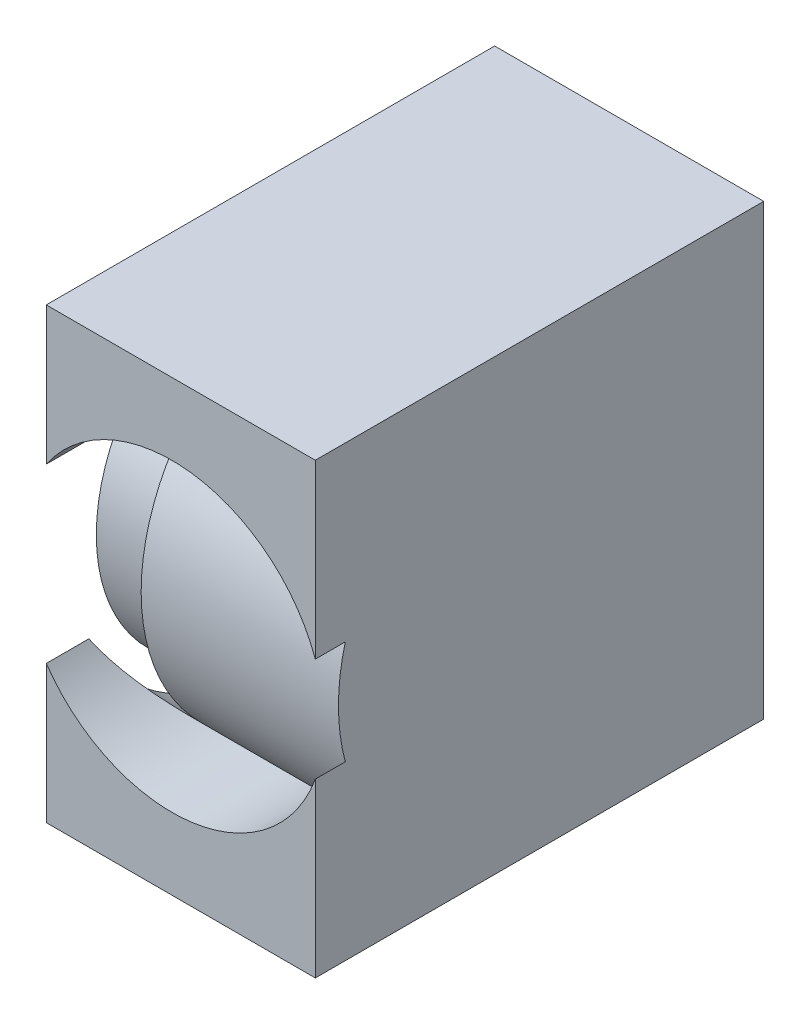
SolidWorks part; units mm, degrees
ref_plane "Front Plane" through (0, 0, 0) normal (0, 0, 1) x (1, 0, 0)
ref_plane "Top Plane" through (0, 0, 0) normal (0, 1, 0) x (1, 0, 0)
ref_plane "Right Plane" through (0, 0, 0) normal (1, 0, 0) x (0, 0, -1)
sketch "Sketch1" plane through (0, 0, 0) normal (1, 0, 0) x (0, 0, -1)
  line L1 (-12.5, 12.5) -> (12.5, 12.5)
  line L2 (-12.5, 12.5) -> (-12.5, -12.5)
  line L3 (-12.5, -12.5) -> (12.5, -12.5)
  line L4 (12.5, 12.5) -> (12.5, -12.5)
  line L5 (-12.5, 12.5) -> (12.5, -12.5) construction
  line L6 (-12.5, -12.5) -> (12.5, 12.5) construction
  point P4 (0, 0)
  dimension "D1" = 25
  dimension "D2" = 25
extrude "Boss-Extrude1" add sketch "Sketch1" along normal blind 15
sketch "Sketch2" plane through (0, 0, 0) normal (-1, 0, 0) x (0, 0, 1)
  circle A0 centre (0, 0) radius 9.71
  circle A1 centre (0, 0) radius 11.21
  dimension "D1" = 19.42
  dimension "D2" = 22.42
extrude "Cut-Extrude1" cut sketch "Sketch2" against normal blind 4
sketch "Sketch4" plane through (0, 0, 12.5) normal (0, 0, 1) x (1, 0, 0)
  circle A0 centre (7.0086, 0) radius 8.5
  dimension "D1" = 17
extrude "Cut-Extrude4" cut sketch "Sketch4" against normal up to surface (1.29 mm away) up to face at (4, 0, 11.21)
